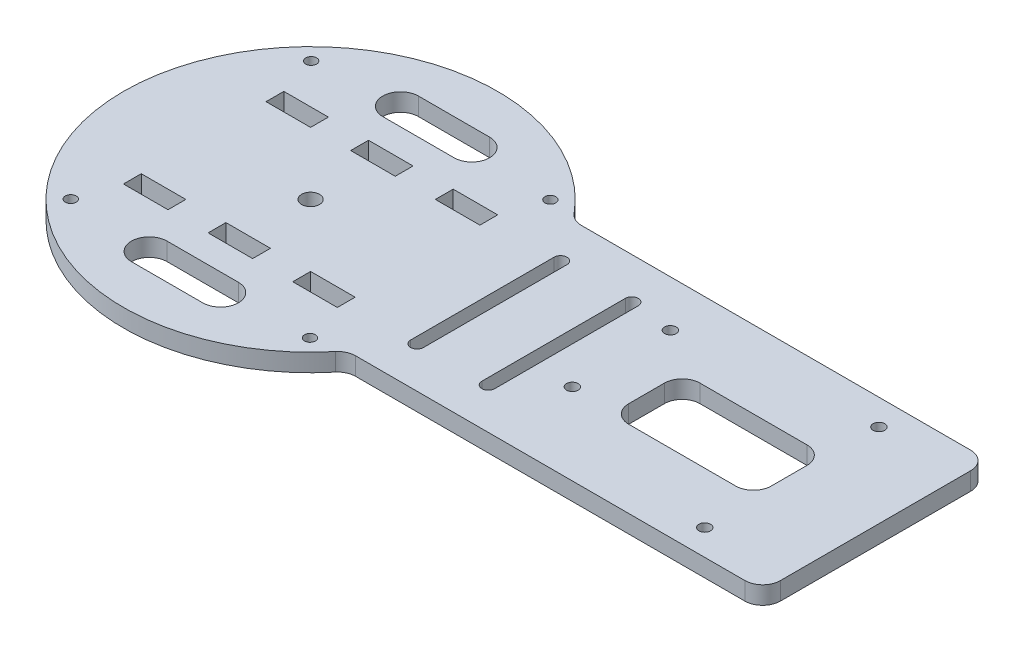
SolidWorks part; units mm, degrees
ref_plane "前视基准面" through (0, 0, 0) normal (0, 0, 1) x (1, 0, 0)
ref_plane "上视基准面" through (0, 0, 0) normal (0, 1, 0) x (1, 0, 0)
ref_plane "右视基准面" through (0, 0, 0) normal (1, 0, 0) x (0, 0, -1)
sketch "草图1" plane through (0, 0, 0) normal (0, 1, 0) x (1, 0, 0)
  line L0 (0, 0) -> (0, 59606) construction
  line L1 (0, 0) -> (59606, 0) construction
  line L2 (30, -22.5) -> (30, -17.5)
  line L3 (-30, 22.5) -> (-17.5, 22.5)
  line L4 (-30, 22.5) -> (-30, 17.5)
  line L5 (-30, 17.5) -> (-17.5, 17.5)
  line L6 (-17.5, 22.5) -> (-17.5, 17.5)
  line L7 (-6.25, 22.5) -> (6.25, 22.5)
  line L8 (-6.25, 22.5) -> (-6.25, 17.5)
  line L9 (-6.25, 17.5) -> (6.25, 17.5)
  line L10 (6.25, 22.5) -> (6.25, 17.5)
  line L11 (17.5, 22.5) -> (30, 22.5)
  line L12 (17.5, 22.5) -> (17.5, 17.5)
  line L13 (17.5, 17.5) -> (30, 17.5)
  line L14 (30, 22.5) -> (30, 17.5)
  line L15 (17.5, -17.5) -> (30, -17.5)
  line L16 (17.5, -22.5) -> (17.5, -17.5)
  line L17 (17.5, -22.5) -> (30, -22.5)
  line L18 (6.25, -22.5) -> (6.25, -17.5)
  line L19 (-6.25, -17.5) -> (6.25, -17.5)
  line L20 (-6.25, -22.5) -> (-6.25, -17.5)
  line L21 (-6.25, -22.5) -> (6.25, -22.5)
  line L22 (-17.5, -22.5) -> (-17.5, -17.5)
  line L23 (-30, -17.5) -> (-17.5, -17.5)
  line L24 (-30, -22.5) -> (-30, -17.5)
  line L25 (-30, -22.5) -> (-17.5, -22.5)
  line L26 (-10, -30.25) -> (10, -30.25)
  line L27 (-10, -40.25) -> (10, -40.25)
  line L28 (-10, 40.25) -> (10, 40.25)
  line L29 (-10, 30.25) -> (10, 30.25)
  line L30 (41.8682, 31.675) -> (158.5, 31.675)
  line L31 (41.8682, -31.675) -> (158.5, -31.675)
  line L32 (158.5, 31.675) -> (158.5, -31.675)
  line L33 (48.1838, 20.1251) -> (48.1838, -20.1251)
  line L34 (51.8162, 20.1251) -> (51.8162, -20.1251)
  line L35 (68.1838, 20.1251) -> (68.1838, -20.1251)
  line L36 (71.8162, 20.1251) -> (71.8162, -20.1251)
  line L38 (94.25, 10) -> (134.25, 10)
  line L39 (94.25, 10) -> (94.25, -10)
  line L40 (94.25, -10) -> (134.25, -10)
  line L41 (134.25, 10) -> (134.25, -10)
  arc A0 (41.8682, 31.675) -> (41.8682, -31.675) centre (0, 0) ccw
  circle A1 centre (-33.5536, 33.7209) radius 1.525
  circle A5 centre (0, 0) radius 2.5
  arc A6 (-10, -30.25) -> (-10, -40.25) centre (-10, -35.25) ccw
  arc A7 (10, -40.25) -> (10, -30.25) centre (10, -35.25) ccw
  arc A8 (10, 40.25) -> (10, 30.25) centre (10, 35.25) cw
  arc A9 (-10, 30.25) -> (-10, 40.25) centre (-10, 35.25) cw
  arc A10 (51.8162, 20.1251) -> (48.1838, 20.1251) centre (50, 20.1251) ccw
  arc A11 (71.8162, 20.1251) -> (68.1838, 20.1251) centre (70, 20.1251) ccw
  arc A12 (71.8162, -20.1251) -> (68.1838, -20.1251) centre (70, -20.1251) cw
  arc A13 (51.8162, -20.1251) -> (48.1838, -20.1251) centre (50, -20.1251) cw
  circle A14 centre (82.254, 18.675) radius 1.625
  circle A15 centre (82.254, -8.825) radius 1.625
  circle A16 centre (135, 24.425) radius 1.625
  circle A17 centre (135, -24.425) radius 1.625
  circle A19 centre (33.7209, 33.5536) radius 1.525
  circle A20 centre (33.5536, -33.7209) radius 1.525
  circle A21 centre (-33.7209, -33.5536) radius 1.525
  point P28 (-6.25, 20)
  point P29 (6.25, 20)
  point P84 (0, 0)
  dimension "D1" = 105
  dimension "D2" = 3.05
  dimension "D10" = 5
  dimension "D11" = 10
  dimension "D21" = 3.25
  dimension "D24" = 3.25
  dimension "D3" = 4
  dimension "D5" = 12.5
  dimension "D6" = 5
  dimension "D7" = 17.5
  dimension "D8" = 11.25
  dimension "D9" = 11.25
  dimension "D12" = 20
  dimension "D13" = 63.35
  dimension "D14" = 50
  dimension "D15" = 20
  dimension "D16" = 20
  dimension "D17" = 40
  dimension "D18" = 24.25
  dimension "D19" = 158.5
  dimension "D20" = 13
  dimension "D22" = 82.254
  dimension "D23" = 27.5
  dimension "D25" = 48.85
  dimension "D26" = 23.5
  dimension "D28" = 70.5
extrude "凸台-拉伸1" add sketch "草图1" along normal blind 5
fillet "圆角1" radius 5 8 edges at (41.8682, 2.5, -31.675) (158.5, 2.5, -31.675) (158.5, 2.5, 31.675) (41.8682, 2.5, 31.675) (134.25, 2.5, 10) (134.25, 2.5, -10) (94.25, 2.5, 10) (94.25, 2.5, -10)
